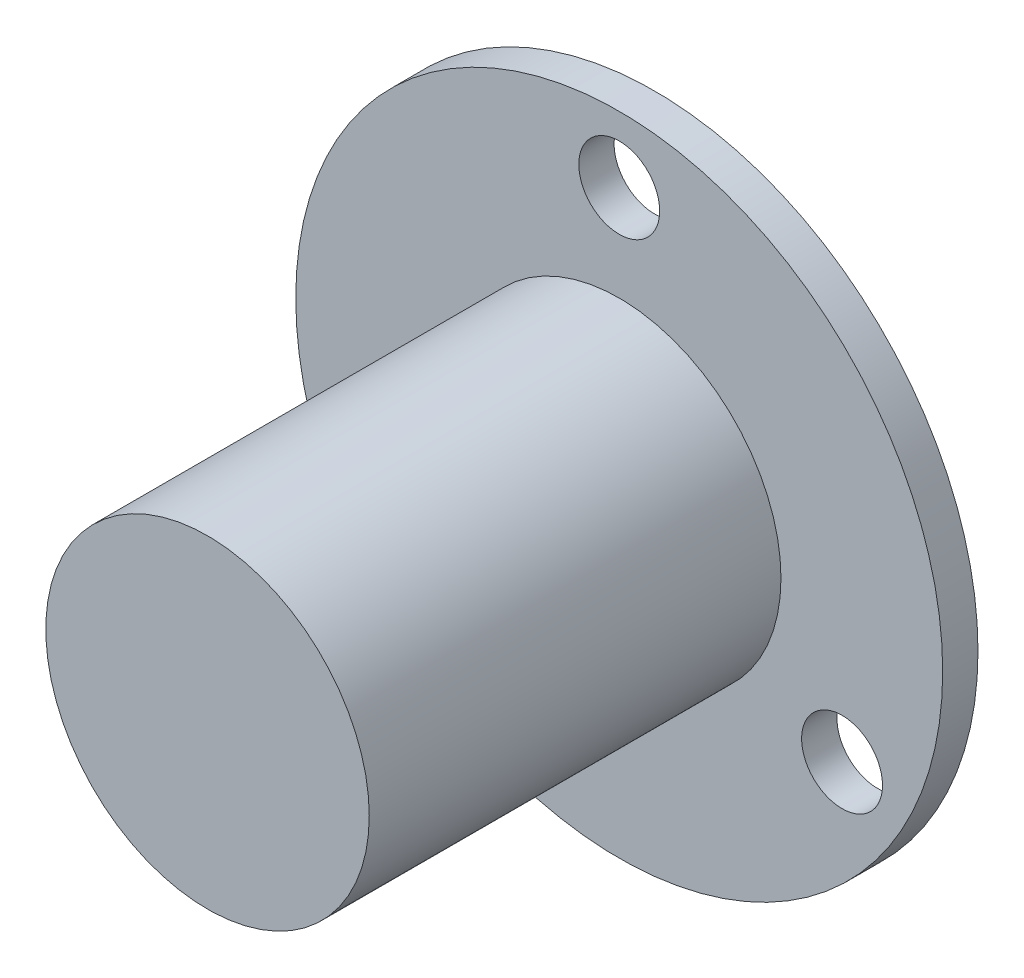
SolidWorks part; units mm, degrees
ref_plane "Front Plane" through (0, 0, 0) normal (0, 0, 1) x (1, 0, 0)
ref_plane "Top Plane" through (0, 0, 0) normal (0, 1, 0) x (1, 0, 0)
ref_plane "Right Plane" through (0, 0, 0) normal (1, 0, 0) x (0, 0, -1)
sketch "Sketch1" plane through (0, 0, 0) normal (0, 0, 1) x (1, 0, 0)
  line L0 (0, 17.5) -> (0, 0) construction
  line L1 (-15.1554, -8.75) -> (0, 0) construction
  line L2 (0, 0) -> (15.1554, -8.75) construction
  circle A0 centre (0, 0) radius 22
  circle A1 centre (0, 0) radius 17.5 construction
  circle A2 centre (0, 17.5) radius 2.75
  circle A3 centre (15.1554, -8.75) radius 2.75
  circle A4 centre (-15.1554, -8.75) radius 2.75
  point P12 (0, 0)
  dimension "D1" = 44
  dimension "D2" = 35
  dimension "D3" = 5.5
  dimension "D6" = 120
  dimension "D5" = 120
  dimension "D4" = 3
extrude "Boss-Extrude1" add sketch "Sketch1" along normal blind 2.4
sketch "Sketch2" plane through (0, 0, 2.4) normal (0, 0, 1) x (1, 0, 0)
  circle A0 centre (0, 0) radius 11
  dimension "D1" = 22
extrude "Boss-Extrude2" add sketch "Sketch2" along normal blind 28
sketch "Sketch3" plane through (0, 0, 0) normal (0, 0, -1) x (-1, 0, 0)
  circle A0 centre (0, 0) radius 3.9
  dimension "D1" = 7.8
extrude "Boss-Extrude3" add sketch "Sketch3" along normal blind 9 contours A0
